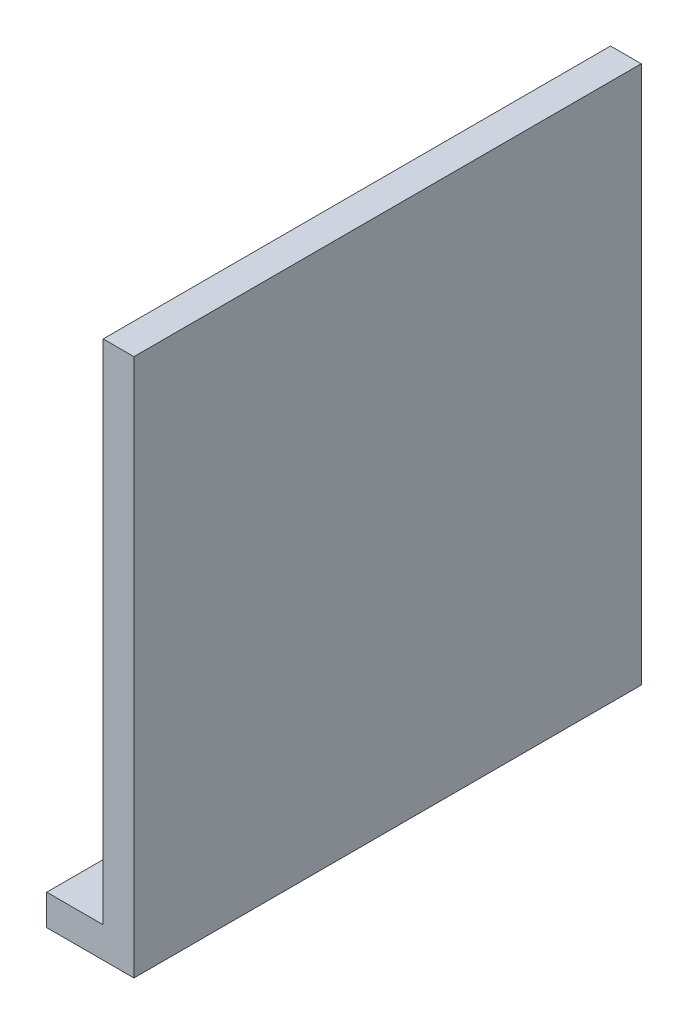
SolidWorks part; units mm, degrees
material "ABS PC"
ref_plane "Front Plane" through (0, 0, 0) normal (0, 0, 1) x (1, 0, 0)
ref_plane "Top Plane" through (0, 0, 0) normal (0, 1, 0) x (1, 0, 0)
ref_plane "Right Plane" through (0, 0, 0) normal (1, 0, 0) x (0, 0, -1)
sketch "Sketch1" plane through (0, 0, 0) normal (0, 1, 0) x (1, 0, 0)
  line L1 (0, 33.02) -> (-11.35, 33.02)
  line L2 (0, 33.02) -> (0, -33.02)
  line L3 (0, -33.02) -> (-11.35, -33.02)
  line L4 (-11.35, 33.02) -> (-11.35, -33.02)
  point P4 (0, 0)
  dimension "D1" = 66.04
  dimension "D2" = 11.35
extrude "Boss-Extrude1" add sketch "Sketch1" along normal blind 4
sketch "Sketch2" plane through (0, 4, 0) normal (0, 1, 0) x (1, 0, 0)
  line L0 (-11.35, -33.02) -> (0, -33.02) construction
  line L1 (0, 33.02) -> (-4, 33.02)
  line L2 (0, 33.02) -> (0, -33.02)
  line L3 (0, -33.02) -> (-4, -33.02)
  line L4 (-4, 33.02) -> (-4, -33.02)
  dimension "D1" = 4
extrude "Boss-Extrude2" add sketch "Sketch2" along normal blind 66.04
sketch "Sketch3" plane through (0, 4, 0) normal (0, 1, 0) x (1, 0, 0)
  line L0 (-7.9035, 25.4) -> (-7.9035, -25.4) construction
  circle A0 centre (-7.9035, 25.4) radius 2.1
  circle A1 centre (-7.9035, -25.4) radius 2.1
  point P4 (-7.9035, 0)
  dimension "D2" = 4.2
  dimension "D3" = 4.2
  dimension "D1" = 50.8
extrude "Cut-Extrude1" cut sketch "Sketch3" against normal up to surface (4 mm away) up to face at (-5.675, 0, 0)
equation "\"D3@Sketch3\"=\"D2@Sketch3\""
